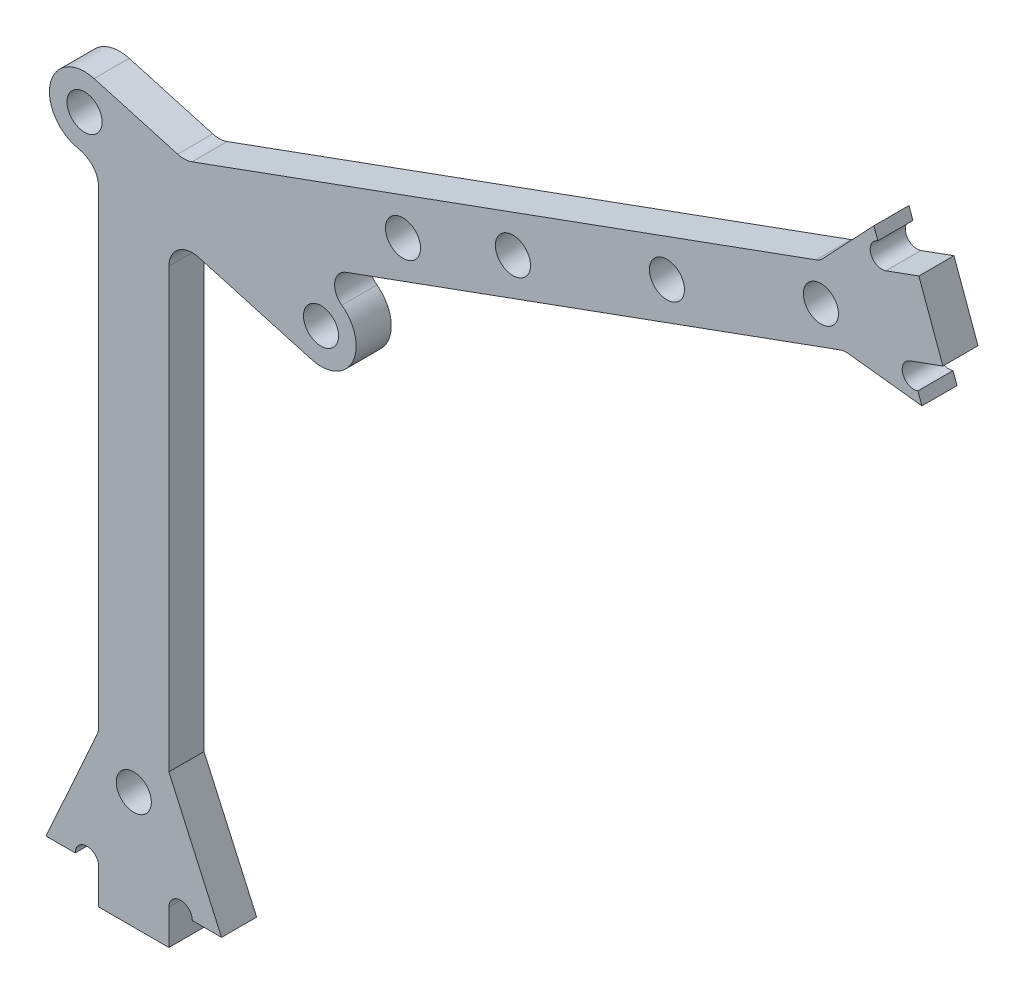
SolidWorks part; units mm, degrees
material "Thornel Mat VMA"
ref_plane "前视基准面" through (0, 0, 0) normal (0, 0, 1) x (1, 0, 0)
ref_plane "上视基准面" through (0, 0, 0) normal (0, 1, 0) x (1, 0, 0)
ref_plane "右视基准面" through (0, 0, 0) normal (1, 0, 0) x (0, 0, -1)
sketch "草图1" plane through (0, 0, 0) normal (0, 0, 1) x (1, 0, 0)
  line L0 (-40.4122, 0) -> (-53.4819, 15.1388) construction
  line L1 (-53.4819, 15.1388) -> (-20.2061, 5.7196) construction
  line L2 (-20.2061, 5.7196) -> (0, 0) construction
  line L3 (-40.4122, 0) -> (-20.2061, 5.7196) construction
  line L4 (-20.2061, 5.7196) -> (13.0697, 15.1388) construction
  line L5 (13.0697, 15.1388) -> (0, 0) construction
  line L6 (-20.2061, 5.7196) -> (0, 0) construction
  line L7 (0, 0) -> (0, -20) construction
  line L8 (0, 0) -> (-7, 0) construction
  line L9 (-7, 0) -> (-7, -50) construction
  line L10 (-7, -21.5) -> (-1, -21.5) construction
  line L11 (-1, -21.5) -> (-1, -246.5) construction
  line L12 (-1, -70) -> (4, -70) construction
  line L13 (4, -70) -> (4, 5) construction
  line L14 (0, 0) -> (4, 5) construction
  line L15 (0, 0) -> (-6.0665, 2.0487) construction
  line L16 (-6.0665, 2.0487) -> (64.4104, 27.7002) construction
  line L17 (64.4104, 27.7002) -> (76.3811, -5.1891) construction
  line L18 (-8.1187, 7.6868) -> (62.3583, 33.3383) construction
  line L19 (-7, -46.5) -> (-13, -46.5) construction
  line L20 (-13, -46.5) -> (-13, -38.5) construction
  line L21 (-13, -38.5) -> (-7, -38.5) construction
  line L22 (0.8171, 2.8866) -> (-1.7601, 3.6161)
  line L23 (-21.0232, 2.833) -> (-19, 2.2603)
  line L24 (-19, -52.5) -> (-19, 2.2603)
  line L25 (-13, -52.5) -> (-13, 0.562)
  line L26 (-19, -52.5) -> (-13, -52.5)
  line L27 (62.3583, 33.3383) -> (-11.6283, 6.4094)
  line L28 (62.3583, 33.3383) -> (64.4104, 27.7002)
  line L29 (64.4104, 27.7002) -> (-1.7601, 3.6161)
  line L30 (-13, 0.562) -> (-0.8171, -2.8866)
  line L31 (-11.6283, 6.4094) -> (-19.389, 8.6062)
  circle A0 centre (0, 0) radius 20 construction
  circle A1 centre (-40.4122, 0) radius 20 construction
  circle A2 centre (0, 0) radius 6.4031 construction
  circle A3 centre (0, 0) radius 70.1142 construction
  circle A4 centre (0, 0) radius 1.5
  arc A5 (-0.8171, -2.8866) -> (0.8171, 2.8866) centre (0, 0) ccw
  circle A6 centre (-20.2061, 5.7196) radius 1.5
  arc A7 (-19.389, 8.6062) -> (-19.8106, 2.7458) centre (-20.2061, 5.7196) ccw
  dimension "D1" = 40
  dimension "D2" = 21
  dimension "D3" = 40
  dimension "D11" = 75
  dimension "D13" = 110
  dimension "D14" = 75
  dimension "D17" = 3
  dimension "D18" = 6
  dimension "D19" = 3
  dimension "D20" = 6
  dimension "D4" = 115
  dimension "D5" = 7
  dimension "D6" = 50
  dimension "D7" = 6
  dimension "D8" = 225
  dimension "D9" = 28.5
  dimension "D10" = 5
  dimension "D12" = 20
  dimension "D15" = 35
  dimension "D16" = 6
  dimension "D21" = 6
  dimension "D22" = 8
  dimension "D23" = 3.5
  dimension "D24" = 6
  dimension "D25" = 6
extrude "凸台-拉伸1" add sketch "草图1" along normal blind 3
fillet "圆角1" radius 2 3 edges at (-19, 2.2603, 1.5) (-11.6283, 6.4094, 1.5) (-13, 0.562, 1.5)
fillet "圆角2" radius 1.5 1 edges at (-1.7601, 3.6161, 1.5)
sketch "草图3" plane through (0, 0, 3) normal (0, 0, 1) x (1, 0, 0)
  line L2 (-19, -52.5) -> (-13, -52.5) construction
  line L4 (-16, -52.5) -> (-16, 7.6469) construction
  line L7 (-21, -49.5) -> (-23.5, -49.5)
  line L8 (-19, -52.5) -> (-19, 0.7479) construction
  line L9 (-23.5, -49.5) -> (-19, -39.5)
  line L10 (-19, -49.5) -> (-19, -39.5)
  line L15 (-12.25, 6.5854) -> (-19.389, 8.6062) construction
  line L16 (-13, -49.5) -> (-13, -39.5)
  line L17 (-8.5, -49.5) -> (-13, -39.5)
  line L18 (-11, -49.5) -> (-8.5, -49.5)
  arc A0 (-19, -49.5) -> (-21, -49.5) centre (-20, -49.5) ccw
  arc A2 (-13, -49.5) -> (-11, -49.5) centre (-12, -49.5) cw
  dimension "D4" = 2
  dimension "D1" = 3
  dimension "D2" = 10
  dimension "D3" = 4.5
extrude "凸台-拉伸2" add sketch "草图3" against normal blind 3
sketch "草图7" plane through (0, 0, 3) normal (0, 0, 1) x (1, 0, 0)
  line L0 (53.1341, 23.5959) -> (64.4104, 27.7002)
  line L1 (64.4104, 27.7002) -> (2.1479, 5.0385) construction
  line L2 (64.4104, 27.7002) -> (62.3583, 33.3383)
  line L3 (62.3583, 33.3383) -> (51.082, 29.2341)
  line L4 (62.3583, 33.3383) -> (-11.0212, 6.6304) construction
  line L5 (51.082, 29.2341) -> (53.1341, 23.5959)
  dimension "D1" = 12
extrude "切除-拉伸2" cut sketch "草图7" against normal blind 10
sketch "草图4" plane through (0, 0, 3) normal (0, 0, 1) x (1, 0, 0)
  line L0 (42.6247, 26.1559) -> (47.2368, 31.0271)
  line L1 (51.082, 29.2341) -> (-11.0212, 6.6304) construction
  line L2 (47.2368, 31.0271) -> (48.2629, 28.208)
  line L3 (48.2629, 28.208) -> (51.082, 29.2341)
  line L4 (51.082, 29.2341) -> (53.1341, 23.5959)
  line L5 (53.1341, 23.5959) -> (50.315, 22.5699)
  line L6 (50.315, 22.5699) -> (51.3411, 19.7508)
  line L7 (51.3411, 19.7508) -> (44.6769, 20.5178)
  line L8 (53.1341, 23.5959) -> (2.1479, 5.0385) construction
  line L9 (44.6769, 20.5178) -> (42.6247, 26.1559)
  line L11 (51.082, 29.2341) -> (53.1341, 23.5959) construction
  dimension "D1" = 3
  dimension "D2" = 9
  dimension "D3" = 3
extrude "凸台-拉伸3" add sketch "草图4" against normal blind 3
fillet "圆角4" radius 1.5 3 edges at (44.6769, 20.5178, 1.5) (42.6247, 26.1559, 1.5) (-19, -39.5, 1.5)
sketch "草图8" plane through (0, 0, 3) normal (0, 0, 1) x (1, 0, 0)
  circle A0 centre (42.7111, 22.9948) radius 1.5
  dimension "D1" = 3
extrude "切除-拉伸3" cut sketch "草图8" against normal blind 3
sketch "草图9" plane through (0, 0, 3) normal (0, 0, 1) x (1, 0, 0)
  line L0 (48.2629, 28.208) -> (47.2368, 31.0271) construction
  line L1 (51.3411, 19.7508) -> (50.315, 22.5699) construction
  circle A0 centre (47.9209, 29.1477) radius 1
  circle A1 centre (50.657, 21.6302) radius 1
  dimension "D1" = 2
  dimension "D2" = 2
extrude "切除-拉伸4" cut sketch "草图9" against normal blind 10
sketch "草图10" plane through (0, 0, 3) normal (0, 0, 1) x (1, 0, 0)
  circle A1 centre (-16, -42.5) radius 1.5
  dimension "D1" = 3
extrude "切除-拉伸5" cut sketch "草图10" against normal blind 10
sketch "草图11" plane through (0, 0, 3) normal (0, 0, 1) x (1, 0, 0)
  line L0 (42.7111, 22.9948) -> (16.3997, 13.4183) construction
  line L1 (16.3997, 13.4183) -> (-2.3941, 6.5778) construction
  circle A1 centre (16.3997, 13.4183) radius 1.5
  circle A2 centre (7.0028, 9.998) radius 1.5
  circle A3 centre (29.5554, 18.2065) radius 1.5
  dimension "D4" = 3
  dimension "D5" = 3
  dimension "D6" = 3
  dimension "D1" = 28
  dimension "D2" = 20
extrude "切除-拉伸6" cut sketch "草图11" against normal through all
